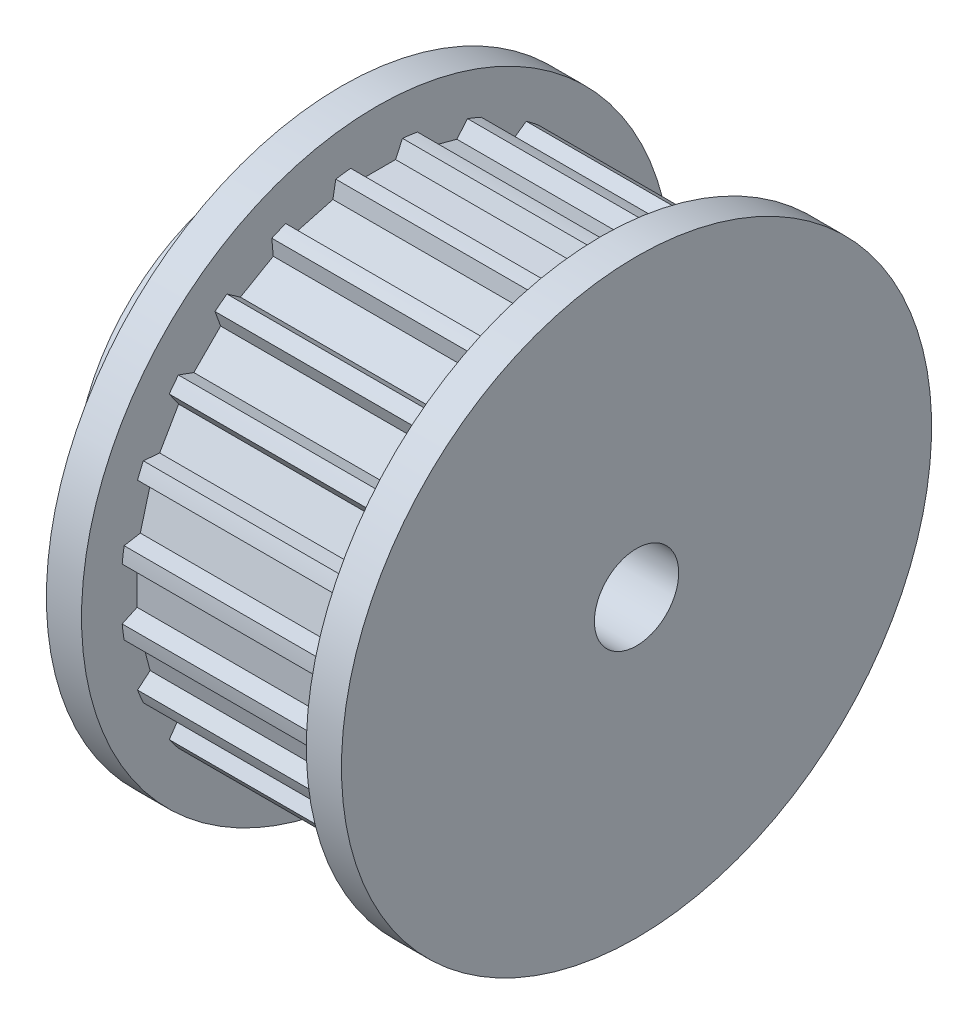
SolidWorks part; units mm, degrees
ref_plane "Front Plane" through (0, 0, 0) normal (0, 0, 1) x (1, 0, 0)
ref_plane "Top Plane" through (0, 0, 0) normal (0, 1, 0) x (1, 0, 0)
ref_plane "Right Plane" through (0, 0, 0) normal (1, 0, 0) x (0, 0, -1)
sketch "Sketch2" plane through (0, 0, 0) normal (1, 0, 0) x (0, 0, -1)
  line L3 (0, 0) -> (0, 17.1) construction
  line L6 (0, -17.2) -> (0, -19.2) construction
  line L7 (-1.3951, 17.1433) -> (-1.35, 17.0466)
  line L8 (1.3951, 17.1433) -> (1.35, 17.0466)
  line L9 (-1.3951, 17.1433) -> (-1.8441, 18.1063)
  line L10 (1.3951, 17.1433) -> (1.8441, 18.1063)
  line L12 (-1.35, 17.0466) -> (1.35, 17.0466)
  line L14 (0, 17.2) -> (0, 19.2) construction
  line L15 (0, 0) -> (0, -4.5) construction
  circle A0 centre (0, 0) radius 19.2 construction
  circle A1 centre (0, 0) radius 17.1 construction
  circle A2 centre (0, 0) radius 17.2 construction
  arc A7 (1.8441, 18.1063) -> (-1.8441, 18.1063) centre (0, 0) ccw
  point P5 (0, 18.2)
  dimension "D1" = 50
  dimension "PD" = 38.4
  dimension "D2" = 2
  dimension "D4" = 2.7
  dimension "D3" = 1.1
  dimension "D5" = 3.6883
  dimension "hs" = 4.5
sketch "Sketch1" plane through (0, 0, 0) normal (0, 0, 1) x (1, 0, 0)
  line L0 (-13.5, 0) -> (13.5, 0) construction
  line L1 (-13.5, 3) -> (13.5, 3)
  line L2 (-13.5, 3) -> (-13.5, 13)
  line L3 (-7.5, 21) -> (-5, 21)
  line L4 (-5, 18.2) -> (-5, 18.45)
  line L5 (-5, 34.8083) -> (-5, 18.2) construction
  line L6 (-5, 18.2) -> (11, 18.2)
  line L7 (11, 18.2) -> (11, 18.45)
  line L8 (-5, 21) -> (-5, 18.45)
  line L9 (11, 21) -> (13.5, 21)
  line L10 (13.5, 21) -> (13.5, 3)
  line L11 (11, 21) -> (11, 18.45)
  line L12 (-10.5, 13) -> (-10.5, 3) construction
  line L13 (-7.5, 21) -> (-7.5, 13)
  line L14 (-7.5, 13) -> (-13.5, 13)
  dimension "Bore Size" = 6
  dimension "Overall Width" = 27
  dimension "Inside Width" = 16
  dimension "Outside Width" = 21
  dimension "Hub Dia" = 26
  dimension "OD" = 42
  dimension "D4" = 0.25
revolve "Revolve1" add sketch "Sketch1" angle 360 mid plane about L0
sketch "Sketch3" plane through (-5, 0, 0) normal (1, 0, 0) x (0, 0, -1)
  line L2 (-1.3951, 17.1433) -> (-1.35, 17.0466) construction
  line L3 (-1.35, 17.0466) -> (1.35, 17.0466) construction
  line L4 (1.3951, 17.1433) -> (1.35, 17.0466) construction
  line L5 (-1.8441, 18.1063) -> (-1.35, 17.0466)
  line L6 (-1.35, 17.0466) -> (1.35, 17.0466)
  line L7 (1.8441, 18.1063) -> (1.35, 17.0466)
  arc A1 (1.8441, 18.1063) -> (-1.8441, 18.1063) centre (0, 0) ccw construction
  arc A2 (1.8441, 18.1063) -> (-1.8441, 18.1063) centre (0, 0) ccw
extrude "Cut-Extrude1" cut sketch "Sketch3" along normal up to surface (16 mm away) up to face at (11, -18.2, 0)
pattern_circular "CirPattern1" count 24 over 360 about axis through (0, 0, 0) along (1, 0, 0) of "Cut-Extrude1"
